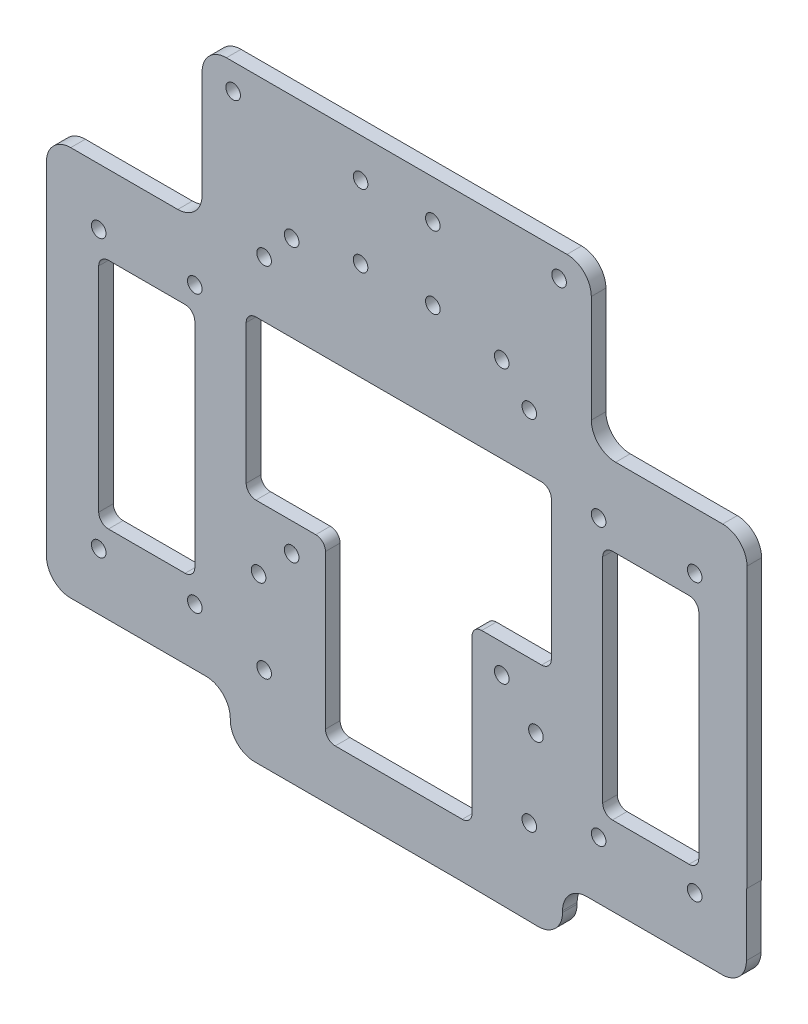
SolidWorks part; units mm, degrees
ref_plane "前视基准面" through (0, 0, 0) normal (0, 0, 1) x (1, 0, 0)
ref_plane "上视基准面" through (0, 0, 0) normal (0, 1, 0) x (1, 0, 0)
ref_plane "右视基准面" through (0, 0, 0) normal (1, 0, 0) x (0, 0, -1)
sketch "草图1" plane through (0, 0, 0) normal (0, 0, 1) x (1, 0, 0)
  line L0 (22.1191, -43.0458) -> (45.1198, -43.0458)
  line L2 (-6.38, 5.2918) -> (73.62, 5.2918)
  line L3 (-6.38, 5.2918) -> (-6.38, -91.7082)
  line L4 (-6.38, -91.7082) -> (73.62, -91.7082)
  line L5 (73.62, 5.2918) -> (73.62, -91.7082)
  line L6 (-6.38, 5.2918) -> (73.62, -91.7082) construction
  line L7 (-6.38, -91.7082) -> (73.62, 5.2918) construction
  circle A0 centre (0, 0) radius 1.5 construction
  circle A1 centre (0, 0) radius 1.5
  circle A2 centre (66.9997, 0.1859) radius 1.5 construction
  circle A3 centre (66.9997, 0.1859) radius 1.5
  circle A4 centre (5.2311, -83.2871) radius 1.5 construction
  circle A5 centre (5.2311, -83.2871) radius 1.5
  circle A6 centre (62.2309, -83.1289) radius 1.5 construction
  circle A7 centre (62.2309, -83.1289) radius 1.5
  circle A8 centre (-24.8798, -43.3705) radius 47 construction
  circle A9 centre (92.1198, -43.0458) radius 47 construction
  point P19 (33.62, -43.2082)
  dimension "D1" = 80
  dimension "D2" = 97
extrude "凸台-拉伸1" add sketch "草图1" along normal blind 3
sketch "草图2" plane through (0, 0, 3) normal (0, 0, 1) x (1, 0, 0)
  line L0 (-6.38, -43.2082) -> (73.62, -43.2082) construction
  line L1 (-6.38, 5.2918) -> (-6.38, -91.7082) construction
  line L2 (73.62, 5.2918) -> (73.62, -91.7082) construction
  line L3 (33.62, 5.2918) -> (33.62, -91.7082) construction
  line L4 (-6.38, 5.2918) -> (73.62, 5.2918) construction
  line L5 (-6.38, -91.7082) -> (73.62, -91.7082) construction
  line L7 (8.22, -0.7882) -> (59.02, -0.7882) construction
  line L8 (8.22, -0.7882) -> (8.22, -85.6282) construction
  line L9 (8.22, -85.6282) -> (59.02, -85.6282) construction
  line L10 (59.02, -0.7882) -> (59.02, -85.6282) construction
  line L11 (8.22, -0.7882) -> (59.02, -85.6282) construction
  line L12 (8.22, -85.6282) -> (59.02, -0.7882) construction
  point P12 (33.62, -43.2082)
  dimension "D1" = 84.84
  dimension "D2" = 50.8
sketch "草图3" plane through (0, 0, 3) normal (0, 0, 1) x (1, 0, 0)
  line L0 (-6.38, -26.7082) -> (-38.38, -26.7082)
  line L1 (-6.38, 5.2918) -> (-6.38, -91.7082) construction
  line L2 (-38.38, -26.7082) -> (-38.38, -89.0861)
  line L3 (-38.38, -89.0861) -> (-6.38, -89.0861)
  line L4 (-6.38, 5.2918) -> (73.62, 5.2918) construction
  line L5 (-6.38, -89.0861) -> (-6.38, -26.7082)
  line L6 (33.62, -91.7082) -> (33.62, -17.4167) construction
  line L7 (-6.38, -91.7082) -> (73.62, -91.7082) construction
  line L8 (105.62, -89.0861) -> (73.62, -89.0861)
  line L9 (105.62, -26.7082) -> (105.62, -89.0861)
  line L10 (73.62, -26.7082) -> (105.62, -26.7082)
  line L11 (73.62, -89.0861) -> (73.62, -26.7082)
  dimension "D1" = 32
  dimension "D2" = 32
extrude "凸台-拉伸2" add sketch "草图3" against normal blind 3
sketch "草图4" plane through (0, 0, 3) normal (0, 0, 1) x (1, 0, 0)
  line L0 (22.1191, -43.0458) -> (45.1198, -43.0458) construction
  line L1 (4.4095, 26.0442) -> (62.8295, 26.0442) construction
  line L2 (4.4095, 26.0442) -> (4.4095, -112.1358) construction
  line L3 (4.4095, -112.1358) -> (62.8295, -112.1358) construction
  line L4 (62.8295, 26.0442) -> (62.8295, -112.1358) construction
  line L5 (4.4095, 26.0442) -> (62.8295, -112.1358) construction
  line L6 (4.4095, -112.1358) -> (62.8295, 26.0442) construction
  line L7 (-38.38, -26.7082) -> (-38.38, -89.0861) construction
  line L8 (-31.38, -33.7082) -> (-4.13, -33.7082) construction
  line L9 (-31.38, -33.7082) -> (-31.38, -99.8982) construction
  line L10 (-31.38, -99.8982) -> (-4.13, -99.8982) construction
  line L11 (-4.13, -33.7082) -> (-4.13, -99.8982) construction
  line L12 (-31.38, -33.7082) -> (-4.13, -99.8982) construction
  line L13 (-31.38, -99.8982) -> (-4.13, -33.7082) construction
  line L14 (-6.38, -26.7082) -> (-38.38, -26.7082) construction
  line L15 (-38.38, -89.0861) -> (-38.38, -106.8982)
  line L16 (-38.38, -106.8982) -> (-4.25, -106.8982)
  line L17 (-4.25, -106.8982) -> (-0.5905, -106.8982)
  line L18 (-0.5905, -106.8982) -> (-0.5905, -117.1358)
  line L19 (-0.5905, -117.1358) -> (20.4738, -117.1358)
  line L21 (20.4738, -117.1358) -> (46.5262, -117.1358)
  line L22 (-38.38, -89.0861) -> (-5.5007, -84.4757)
  line L23 (-5.5007, -84.4757) -> (11.9909, -90.3487)
  line L24 (11.9909, -90.3487) -> (55.0091, -90.3487)
  line L25 (105.5, -89.0861) -> (105.5, -106.9913)
  line L26 (105.5, -89.0861) -> (72.5007, -84.4757)
  line L27 (72.5007, -84.4757) -> (55.0091, -90.3487)
  line L28 (67.71, -117.3913) -> (46.5262, -117.1358)
  line L29 (67.71, -106.9913) -> (67.71, -117.3913)
  line L30 (71.25, -106.9913) -> (67.71, -106.9913)
  line L31 (105.5, -106.9913) -> (71.25, -106.9913)
  point P0 (33.6195, -43.0458)
  point P7 (-17.755, -66.8032)
  dimension "D1" = 58.42
  dimension "D2" = 138.18
  dimension "D3" = 27.25
  dimension "D4" = 66.19
  dimension "D5" = 7
  dimension "D6" = 7
  dimension "D7" = 7
  dimension "D8" = 5
  dimension "D9" = 5
extrude "凸台-拉伸3" add sketch "草图4" against normal blind 3
sketch "草图5" plane through (0, 0, 3) normal (0, 0, 1) x (1, 0, 0)
  line L0 (-31.38, -99.8982) -> (-4.13, -33.7082) construction
  line L1 (-27.63, -38.3882) -> (-7.88, -38.3882) construction
  line L2 (-27.63, -38.3882) -> (-27.63, -95.2182) construction
  line L3 (-27.63, -95.2182) -> (-7.88, -95.2182) construction
  line L4 (-7.88, -38.3882) -> (-7.88, -95.2182) construction
  line L5 (-27.63, -38.3882) -> (-7.88, -95.2182) construction
  line L6 (-27.63, -95.2182) -> (-7.88, -38.3882) construction
  line L7 (33.62, 5.2918) -> (33.62, -32.0821) construction
  line L8 (-6.38, 5.2918) -> (73.62, 5.2918) construction
  line L9 (94.87, -95.2182) -> (75.12, -38.3882) construction
  line L10 (94.87, -38.3882) -> (75.12, -95.2182) construction
  line L11 (75.12, -38.3882) -> (75.12, -95.2182) construction
  line L12 (94.87, -95.2182) -> (75.12, -95.2182) construction
  line L13 (94.87, -38.3882) -> (94.87, -95.2182) construction
  line L14 (94.87, -38.3882) -> (75.12, -38.3882) construction
  circle A0 centre (-27.63, -38.3882) radius 1.5
  circle A1 centre (-7.88, -38.3882) radius 1.5
  circle A2 centre (-27.63, -95.2182) radius 1.5
  circle A3 centre (-7.88, -95.2182) radius 1.5
  circle A4 centre (75.12, -95.2182) radius 1.5
  circle A5 centre (94.87, -95.2182) radius 1.5
  circle A6 centre (75.12, -38.3882) radius 1.5
  circle A7 centre (94.87, -38.3882) radius 1.5
  point P0 (-17.755, -66.8032)
  point P23 (84.995, -66.8032)
  dimension "D3" = 3
  dimension "D4" = 3
  dimension "D5" = 3
  dimension "D6" = 3
  dimension "D1" = 19.75
  dimension "D2" = 56.83
extrude "切除-拉伸2" cut sketch "草图5" against normal blind 3
sketch "草图6" plane through (0, 0, 3) normal (0, 0, 1) x (1, 0, 0)
  line L0 (33.62, -43.2082) -> (33.62, -53.2082) construction
  line L1 (12.03, -20.1432) -> (55.21, -20.1432) construction
  line L2 (12.03, -20.1432) -> (12.03, -76.2732) construction
  line L3 (12.03, -76.2732) -> (55.21, -76.2732) construction
  line L4 (55.21, -20.1432) -> (55.21, -76.2732) construction
  line L5 (12.03, -20.1432) -> (55.21, -76.2732) construction
  line L6 (12.03, -76.2732) -> (55.21, -20.1432) construction
  line L7 (-6.38, -91.7082) -> (73.62, 5.2918) construction
  circle A0 centre (12.03, -20.1432) radius 1.5
  circle A1 centre (55.21, -20.1432) radius 1.5
  circle A2 centre (12.03, -76.2732) radius 1.5
  circle A3 centre (55.21, -76.2732) radius 1.5
  point P0 (33.62, -48.2082)
  dimension "D4" = 3
  dimension "D5" = 3
  dimension "D6" = 3
  dimension "D7" = 3
  dimension "D1" = 43.18
  dimension "D2" = 56.13
  dimension "D3" = 5
extrude "切除-拉伸4" cut sketch "草图6" against normal blind 3
fillet "圆角1" radius 5 11 edges at (-38.38, -106.8982, 1.5) (-0.5905, -117.1358, 1.5) (-0.5905, -106.8982, 1.5) (67.71, -106.9913, 1.5) (105.5, -106.9913, 1.5) (105.62, -26.7082, 1.5) (73.62, -26.7082, 1.5) (73.62, 5.2918, 1.5) (-6.38, 5.2918, 1.5) (-6.38, -26.7082, 1.5) (-38.38, -26.7082, 1.5)
fillet "圆角2" radius 5 1 edges at (67.71, -117.3913, 1.5)
sketch "草图8" plane through (0, 0, 3) normal (0, 0, 1) x (1, 0, 0)
  line L0 (-27.63, -38.3882) -> (-7.88, -95.2182) construction
  line L1 (-25.63, -42.8843) -> (-9.88, -42.8843)
  line L2 (-27.63, -44.8843) -> (-27.63, -88.722)
  line L3 (-25.63, -90.722) -> (-9.88, -90.722)
  line L4 (-7.88, -44.8843) -> (-7.88, -88.722)
  line L5 (-27.63, -42.8843) -> (-7.88, -90.722) construction
  line L6 (-27.63, -90.722) -> (-7.88, -42.8843) construction
  line L7 (-7.88, -38.3882) -> (-7.88, -95.2182) construction
  line L9 (20.9818, -2.2137) -> (47.0985, -2.2137)
  line L10 (18.9818, -4.2137) -> (18.9818, -35.8223)
  line L11 (20.9818, -106.0277) -> (47.0985, -106.0277)
  line L12 (49.0985, -4.2137) -> (49.0985, -35.8223)
  line L13 (18.9818, -2.2137) -> (29.3119, -37.8223) construction
  line L14 (18.9818, -106.0277) -> (29.3119, -70.4192) construction
  line L15 (4.6833, -37.8223) -> (16.9818, -37.8223)
  line L16 (2.6833, -39.8223) -> (2.6833, -68.4192)
  line L17 (4.6833, -70.4192) -> (16.9818, -70.4192)
  line L18 (65.3969, -39.8223) -> (65.3969, -68.4192)
  line L19 (2.6833, -37.8223) -> (18.9818, -46.2938) construction
  line L20 (2.6833, -70.4192) -> (34.0401, -54.1207) construction
  line L21 (18.9818, -72.4192) -> (18.9818, -104.0277)
  line L22 (49.0985, -61.9477) -> (65.3969, -70.4192) construction
  line L23 (93.7102, -90.722) -> (77.9602, -90.722)
  line L24 (38.7683, -37.8223) -> (49.0985, -2.2137) construction
  line L25 (49.0985, -72.4192) -> (49.0985, -104.0277)
  line L26 (51.0985, -37.8223) -> (63.3969, -37.8223)
  line L27 (51.0985, -70.4192) -> (63.3969, -70.4192)
  line L28 (75.9602, -44.8843) -> (75.9602, -88.722)
  line L29 (93.7102, -42.8843) -> (77.9602, -42.8843)
  line L30 (95.7102, -44.8843) -> (95.7102, -88.722)
  arc A0 (-27.63, -88.722) -> (-25.63, -90.722) centre (-25.63, -88.722) ccw
  arc A1 (-9.88, -90.722) -> (-7.88, -88.722) centre (-9.88, -88.722) ccw
  arc A2 (-7.88, -44.8843) -> (-9.88, -42.8843) centre (-9.88, -44.8843) ccw
  arc A3 (-27.63, -44.8843) -> (-25.63, -42.8843) centre (-25.63, -44.8843) cw
  arc A4 (77.9602, -90.722) -> (75.9602, -88.722) centre (77.9602, -88.722) cw
  arc A5 (75.9602, -44.8843) -> (77.9602, -42.8843) centre (77.9602, -44.8843) cw
  arc A6 (95.7102, -88.722) -> (93.7102, -90.722) centre (93.7102, -88.722) cw
  arc A7 (95.7102, -44.8843) -> (93.7102, -42.8843) centre (93.7102, -44.8843) ccw
  arc A8 (47.0985, -2.2137) -> (49.0985, -4.2137) centre (47.0985, -4.2137) cw
  arc A9 (49.0985, -35.8223) -> (51.0985, -37.8223) centre (51.0985, -35.8223) ccw
  arc A10 (63.3969, -37.8223) -> (65.3969, -39.8223) centre (63.3969, -39.8223) cw
  arc A11 (65.3969, -68.4192) -> (63.3969, -70.4192) centre (63.3969, -68.4192) cw
  arc A12 (51.0985, -70.4192) -> (49.0985, -72.4192) centre (51.0985, -72.4192) ccw
  arc A13 (49.0985, -104.0277) -> (47.0985, -106.0277) centre (47.0985, -104.0277) cw
  arc A14 (20.9818, -106.0277) -> (18.9818, -104.0277) centre (20.9818, -104.0277) cw
  arc A15 (18.9818, -72.4192) -> (16.9818, -70.4192) centre (16.9818, -72.4192) ccw
  arc A16 (4.6833, -70.4192) -> (2.6833, -68.4192) centre (4.6833, -68.4192) cw
  arc A17 (2.6833, -39.8223) -> (4.6833, -37.8223) centre (4.6833, -39.8223) cw
  arc A18 (16.9818, -37.8223) -> (18.9818, -35.8223) centre (16.9818, -35.8223) ccw
  arc A19 (18.9818, -4.2137) -> (20.9818, -2.2137) centre (20.9818, -4.2137) cw
  point P0 (-17.755, -66.8032)
  point P21 (34.0401, -54.1207)
  point P26 (34.0401, -54.1207)
  point P58 (49.0985, -37.8223)
  point P66 (49.0985, -70.4192)
  dimension "D1" = 2
  dimension "D2" = 2
extrude "切除-拉伸5" cut sketch "草图8" against normal blind 10
sketch "草图9" plane through (0, 0, 3) normal (0, 0, 1) x (1, 0, 0)
  line L0 (34.9674, 11.7958) -> (35.0784, -28.204) construction
  line L5 (17.272, 2.8621) -> (52.8253, 2.8621)
  line L6 (17.272, 2.8621) -> (17.272, -37.8223)
  line L7 (17.272, -37.8223) -> (52.8253, -37.8223)
  line L8 (52.8253, 2.8621) -> (52.8253, -37.8223)
  line L9 (17.272, 2.8621) -> (52.8253, -37.8223) construction
  line L10 (17.272, -37.8223) -> (52.8253, 2.8621) construction
  line L11 (63.3969, -37.8223) -> (51.0985, -37.8223) construction
  point P0 (8.22, -0.7882)
  point P1 (35.0486, -17.4801)
extrude "凸台-拉伸4" add sketch "草图9" against normal up to surface (3 mm away) contours L6 L5 L8 L7 up to face at (-17.755, -66.8032, 0)
sketch "草图10" plane through (0, 0, 3) normal (0, 0, 1) x (1, 0, 0)
  line L0 (33.62, 5.2918) -> (33.62, -117.1358) construction
  line L1 (4.4095, -117.1358) -> (46.5262, -117.1358) construction
  circle A0 centre (6.37, -26.2985) radius 1.5
  circle A1 centre (60.87, -26.2985) radius 1.5
  circle A2 centre (6.37, -99.7985) radius 1.5
  circle A3 centre (60.87, -99.7985) radius 1.5
  point P13 (0, 0)
  point P14 (0, 0)
  dimension "D1" = 54.5
  dimension "D2" = 73.5
extrude "切除-拉伸6" cut sketch "草图10" against normal up to next contours A1 | A0 | A2 | A3
sketch "草图11" plane through (0, 0, 3) normal (0, 0, 1) x (1, 0, 0)
  line L0 (33.62, 5.2918) -> (33.62, -91.7082) construction
  line L1 (33.62, 5.2918) -> (33.62, -23.9253) construction
  circle A0 centre (26.195, -2.7148) radius 1.5
  circle A1 centre (41.045, -2.7148) radius 1.5
  circle A2 centre (26.195, -17.5648) radius 1.5
  circle A3 centre (41.045, -17.5648) radius 1.5
  point P15 (0, 0)
  dimension "D1" = 14.85
  dimension "D2" = 3
  dimension "D3" = 14.85
extrude "切除-拉伸7" cut sketch "草图11" against normal up to next contours A0 | A3 | A1 | A2
